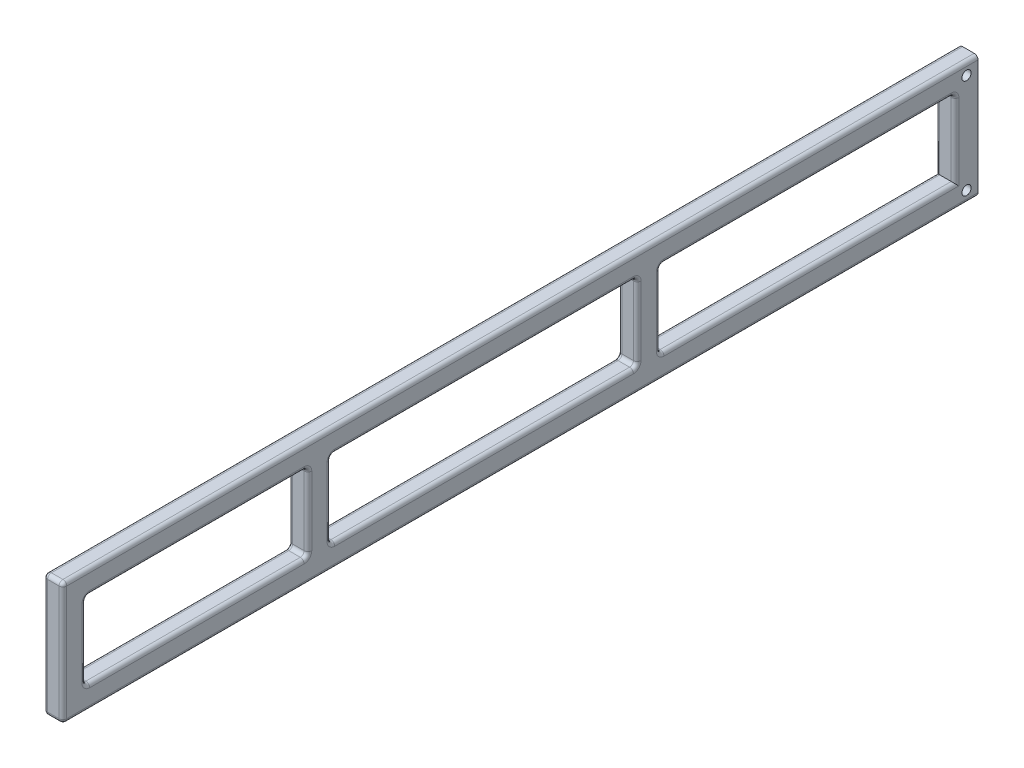
SolidWorks part; units mm, degrees
ref_plane "Plano frontal" through (0, 0, 0) normal (0, 0, 1) x (1, 0, 0)
ref_plane "Plano superior" through (0, 0, 0) normal (0, 1, 0) x (1, 0, 0)
ref_plane "Plano direito" through (0, 0, 0) normal (1, 0, 0) x (0, 0, -1)
sketch "Esboço8" plane through (0, 0, 0) normal (1, 0, 0) x (0, 0, -1)
  line L0 (-88.4414, 36) -> (-8.4414, 36)
  line L1 (80.5586, 10) -> (-158.4414, 10)
  line L3 (74.5586, 16) -> (-2.4414, 16)
  line L5 (-158.4414, 42) -> (48.3024, 42)
  line L7 (-152.4414, 36) -> (-94.4414, 36)
  line L8 (74.5586, 36) -> (74.5586, 16)
  line L10 (-94.4414, 36) -> (-94.4414, 16)
  line L12 (-88.4414, 36) -> (-88.4414, 16)
  line L14 (-2.4414, 36) -> (-2.4414, 16)
  line L16 (-8.4414, 36) -> (-8.4414, 16)
  line L17 (-94.4414, 16) -> (-152.4414, 16)
  line L18 (-2.4414, 36) -> (74.5586, 36)
  line L19 (-8.4414, 16) -> (-88.4414, 16)
  line L20 (-158.4414, 42) -> (-158.4414, 10)
  line L22 (-152.4414, 16) -> (-152.4414, 36)
  line L24 (48.3024, 42) -> (80.5586, 42)
  line L25 (80.5586, 42) -> (80.5586, 10)
  line L26 (-158.4414, 46.9478) -> (-158.4414, 63.5278) construction
  line L27 (-73.4414, 23.5684) -> (-73.4414, 49.1501) construction
  line L28 (-88.4414, 29.3226) -> (-88.4414, 53.5202) construction
  dimension "D2" = 239
  dimension "D3" = 80
  dimension "D4" = 0
  dimension "D5" = 6
  dimension "D6" = 20
  dimension "D8" = 6
  dimension "D9" = 6
  dimension "D10" = 6
extrude "Ressalto-extrusão1" add sketch "Esboço8" against normal blind 5
fillet "Filete1" radius 1 43 edges at (-5, 26, -74.5586) (0, 26, -74.5586) (-5, 26, 152.4414) (0, 26, 152.4414) (-5, 26, 94.4414) (0, 26, 94.4414) (-5, 26, 88.4414) (0, 26, 88.4414) (-5, 26, 8.4414) (0, 26, 8.4414) (-5, 16, -36.0586) (0, 16, -36.0586) (-2.5, 36, -74.5586) (-5, 36, -36.0586) (0, 36, -36.0586) (-2.5, 36, 8.4414) (-5, 36, 48.4414) (-2.5, 36, 88.4414) (0, 36, 48.4414) (-2.5, 36, 94.4414) (-5, 36, 123.4414) (-2.5, 36, 152.4414) (0, 36, 123.4414) (-2.5, 16, 152.4414) (-5, 16, 123.4414) (-2.5, 16, 94.4414) (0, 16, 123.4414) (-2.5, 16, 88.4414) (-5, 16, 48.4414) (-2.5, 16, 8.4414) (0, 16, 48.4414) (-2.5, 36, 2.4414) (-5, 26, 2.4414) (-2.5, 16, 2.4414) (0, 26, 2.4414) (0, 26, 158.4414) (-5, 10, 38.9414) (0, 10, 38.9414) (-5, 42, 38.9414) (0, 42, 38.9414) (-2.5, 10, 158.4414) (-5, 26, 158.4414) (-2.5, 42, 158.4414)
sketch "Esboço9" plane through (0, 0, 0) normal (1, 0, 0) x (0, 0, -1)
  circle A2 centre (77.5687, 13) radius 1.2
  circle A3 centre (77.5586, 39) radius 1.2
  dimension "D1" = 2.4
  dimension "D2" = 2.4
extrude "Corte-extrusão1" cut sketch "Esboço9" against normal blind 4
